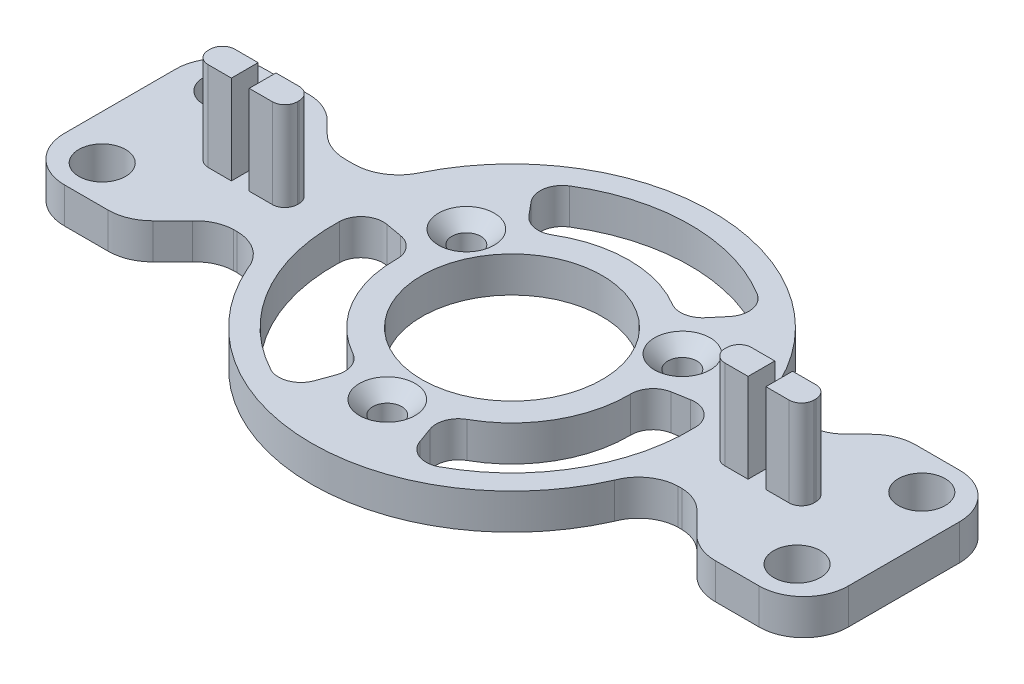
SolidWorks part; units mm, degrees
ref_plane "Front Plane" through (0, 0, 0) normal (0, 0, 1) x (1, 0, 0)
ref_plane "Top Plane" through (0, 0, 0) normal (0, 1, 0) x (1, 0, 0)
ref_plane "Right Plane" through (0, 0, 0) normal (1, 0, 0) x (0, 0, -1)
sketch "Sketch1" plane through (0, 0, 0) normal (0, 1, 0) x (1, 0, 0)
  line L0 (-12.1244, 7) -> (0, 0) construction
  line L1 (0, 0) -> (12.1244, 7) construction
  line L2 (0, 0) -> (0, -14) construction
  line L3 (-34.0711, 11.252) -> (-39, 11.252)
  line L4 (-34.0711, -11.252) -> (-39, -11.252)
  line L5 (-44, 6.252) -> (-44, -6.252)
  line L6 (-30.5355, 9.7875) -> (-29.2125, 8.4645)
  line L7 (-25.6769, 7) -> (-24.7437, 7)
  line L8 (-30.5355, -9.7875) -> (-28.3139, -7.5659)
  line L9 (-24.76, -6.1015) -> (-25.1596, -6.1015)
  line L11 (-5.2752, -14.4935) -> (-5.924, -16.276)
  line L12 (-9.9142, 11.8152) -> (-11.1334, 13.2683)
  line L13 (0, -55) -> (0, 55) construction
  line L14 (-15.1894, 2.6783) -> (-17.0574, 3.0077)
  line L15 (9.9142, 11.8152) -> (11.1334, 13.2683)
  line L16 (15.1894, 2.6783) -> (17.0574, 3.0077)
  line L17 (5.2752, -14.4935) -> (5.924, -16.276)
  line L18 (24.76, -6.1015) -> (25.1596, -6.1015)
  line L19 (30.5355, -9.7875) -> (28.3139, -7.5659)
  line L20 (34.0711, -11.252) -> (39, -11.252)
  line L21 (44, 6.252) -> (44, -6.252)
  line L22 (34.0711, 11.252) -> (39, 11.252)
  line L23 (30.5355, 9.7875) -> (29.2125, 8.4645)
  line L24 (25.6769, 7) -> (24.7437, 7)
  arc A0 (-19.4844, -11.252) -> (20.5852, -9.083) centre (0, 0) ccw
  circle A1 centre (0, 0) radius 10.125
  circle A2 centre (-12.1244, 7) radius 1.625
  circle A3 centre (12.1244, 7) radius 1.625
  circle A4 centre (0, -14) radius 1.625
  circle A5 centre (-39, 7) radius 2.625
  circle A6 centre (-39, -7) radius 2.625
  arc A7 (-19.4844, 11.252) -> (-20.2448, 9.8182) centre (0, 0) ccw
  arc A8 (-20.5852, -9.083) -> (-19.4844, -11.252) centre (0, 0) ccw
  arc A10 (-24.7437, 7) -> (-20.2448, 9.8182) centre (-24.7437, 12) ccw
  arc A12 (-29.2125, 8.4645) -> (-25.6769, 7) centre (-25.6769, 12) ccw
  arc A13 (-30.5355, 9.7875) -> (-34.0711, 11.252) centre (-34.0711, 6.252) ccw
  arc A14 (-30.5355, -9.7875) -> (-34.0711, -11.252) centre (-34.0711, -6.252) cw
  arc A15 (-39, -11.252) -> (-44, -6.252) centre (-39, -6.252) cw
  arc A16 (-39, 11.252) -> (-44, 6.252) centre (-39, 6.252) ccw
  arc A18 (-19.9903, 0.6236) -> (-9.4551, -17.6239) centre (0, 0) ccw
  arc A19 (6.7192, 11.2747) -> (9.9142, 11.8152) centre (7.9991, 13.4222) ccw
  arc A20 (10.5352, 17.0003) -> (-10.5352, 17.0003) centre (0, 0) ccw
  arc A21 (11.1334, 13.2683) -> (10.5352, 17.0003) centre (9.2183, 14.8752) ccw
  arc A22 (6.7192, 11.2747) -> (-6.7192, 11.2747) centre (0, 0) ccw
  arc A23 (-13.1237, 0.1817) -> (-6.4045, -11.4563) centre (0, 0) ccw
  arc A24 (-11.1334, 13.2683) -> (-10.5352, 17.0003) centre (-9.2183, 14.8752) cw
  arc A25 (-6.7192, 11.2747) -> (-9.9142, 11.8152) centre (-7.9991, 13.4222) cw
  arc A26 (-5.924, -16.276) -> (-9.4551, -17.6239) centre (-8.2732, -15.4209) cw
  arc A27 (-5.2752, -14.4935) -> (-6.4045, -11.4563) centre (-7.6244, -13.6385) ccw
  arc A28 (-15.1894, 2.6783) -> (-13.1237, 0.1817) centre (-15.6235, 0.2163) cw
  arc A29 (-17.0574, 3.0077) -> (-19.9903, 0.6236) centre (-17.4915, 0.5457) ccw
  arc A30 (13.1237, 0.1817) -> (6.4045, -11.4563) centre (0, 0) cw
  arc A31 (15.1894, 2.6783) -> (13.1237, 0.1817) centre (15.6235, 0.2163) ccw
  arc A32 (17.0574, 3.0077) -> (19.9903, 0.6236) centre (17.4915, 0.5457) cw
  arc A33 (19.9903, 0.6236) -> (9.4551, -17.6239) centre (0, 0) cw
  arc A34 (5.924, -16.276) -> (9.4551, -17.6239) centre (8.2732, -15.4209) ccw
  arc A35 (5.2752, -14.4935) -> (6.4045, -11.4563) centre (7.6244, -13.6385) cw
  arc A38 (30.5355, -9.7875) -> (34.0711, -11.252) centre (34.0711, -6.252) ccw
  arc A39 (39, -11.252) -> (44, -6.252) centre (39, -6.252) ccw
  arc A40 (39, 11.252) -> (44, 6.252) centre (39, 6.252) cw
  arc A41 (30.5355, 9.7875) -> (34.0711, 11.252) centre (34.0711, 6.252) cw
  arc A42 (29.2125, 8.4645) -> (25.6769, 7) centre (25.6769, 12) cw
  arc A43 (24.7437, 7) -> (20.2448, 9.8182) centre (24.7437, 12) cw
  circle A44 centre (39, -7) radius 2.625
  circle A45 centre (39, 7) radius 2.625
  arc A46 (20.2448, 9.8182) -> (-19.4844, 11.252) centre (0, 0) ccw
  arc A47 (-28.3139, -7.5659) -> (-25.1596, -6.1015) centre (-25.0358, -10.4975) cw
  arc A48 (-24.76, -6.1015) -> (-20.5852, -9.083) centre (-24.76, -10.5151) cw
  arc A49 (20.5852, -9.083) -> (24.76, -6.1015) centre (24.8797, -10.6826) cw
  arc A50 (25.1596, -6.1015) -> (28.3139, -7.5659) centre (25.0665, -10.4312) cw
  point P25 (-21.6569, -6.1015)
  point P34 (-32, 11.252)
  point P37 (-32, -11.252)
  point P40 (-44, -11.252)
  point P43 (-44, 11.252)
  point P56 (12.8558, 15.3209)
  point P92 (32, -11.252)
  dimension "D1" = 45
  dimension "D2" = 20.25
  dimension "D3" = 3.25
  dimension "D4" = 3.25
  dimension "D5" = 3.25
  dimension "D13" = 5.25
  dimension "D14" = 5.25
  dimension "D24" = 2.5
  dimension "D25" = 2.5
  dimension "D26" = 60
  dimension "D6" = 14
  dimension "D7" = 14
  dimension "D8" = 14
  dimension "D9" = 120
  dimension "D10" = 120
  dimension "D11" = 44
  dimension "D12" = 44
  dimension "D15" = 39
  dimension "D16" = 39
  dimension "D17" = 7
  dimension "D18" = 7
  dimension "D19" = 12
  dimension "D20" = 12
  dimension "D21" = 135
  dimension "D22" = 135
  dimension "D27" = 20
  dimension "D28" = 20
extrude "Boss-Extrude1" add sketch "Sketch1" along normal blind 4
sketch "Sketch2" plane through (0, 4, 0) normal (0, 1, 0) x (1, 0, 0)
  line L0 (-44, 6.252) -> (-44, -6.252) construction
  line L9 (-32.6, 1.5) -> (-30, 1.5)
  line L10 (-34, 0.1) -> (-34, -0.1)
  line L11 (-32.6, -1.5) -> (-30, -1.5)
  line L12 (-30, 1.5) -> (-30, -1.5)
  line L13 (-28, 1.5) -> (-25.4, 1.5)
  line L14 (-28, 1.5) -> (-28, -1.5)
  line L15 (-28, -1.5) -> (-25.4, -1.5)
  line L16 (-24, 0.1) -> (-24, -0.1)
  arc A0 (-25.4, 1.5) -> (-24, 0.1) centre (-25.4, 0.1) cw
  arc A1 (-25.4, -1.5) -> (-24, -0.1) centre (-25.4, -0.1) ccw
  arc A2 (-34, -0.1) -> (-32.6, -1.5) centre (-32.6, -0.1) ccw
  arc A3 (-32.6, 1.5) -> (-34, 0.1) centre (-32.6, 0.1) ccw
  point P13 (-24, 1.5)
  point P16 (-24, -1.5)
  point P19 (-34, -1.5)
  point P22 (-34, 1.5)
  dimension "D9" = 1.4
  dimension "D1" = 2
  dimension "D2" = 3
  dimension "D3" = 3
  dimension "D4" = 1.5
  dimension "D5" = 1.5
  dimension "D6" = 10
  dimension "D7" = 4
  dimension "D8" = 4
extrude "Boss-Extrude2" add sketch "Sketch2" along normal blind 10
mirror "Mirror1" about plane through (0, 0, 0) normal (1, 0, 0) of "Boss-Extrude2"
chamfer "Chamfer1" distance 1.5 angle 45 3 edges at (12.1244, 4, -5.375) (0, 4, 15.625) (-12.1244, 4, -5.375)
